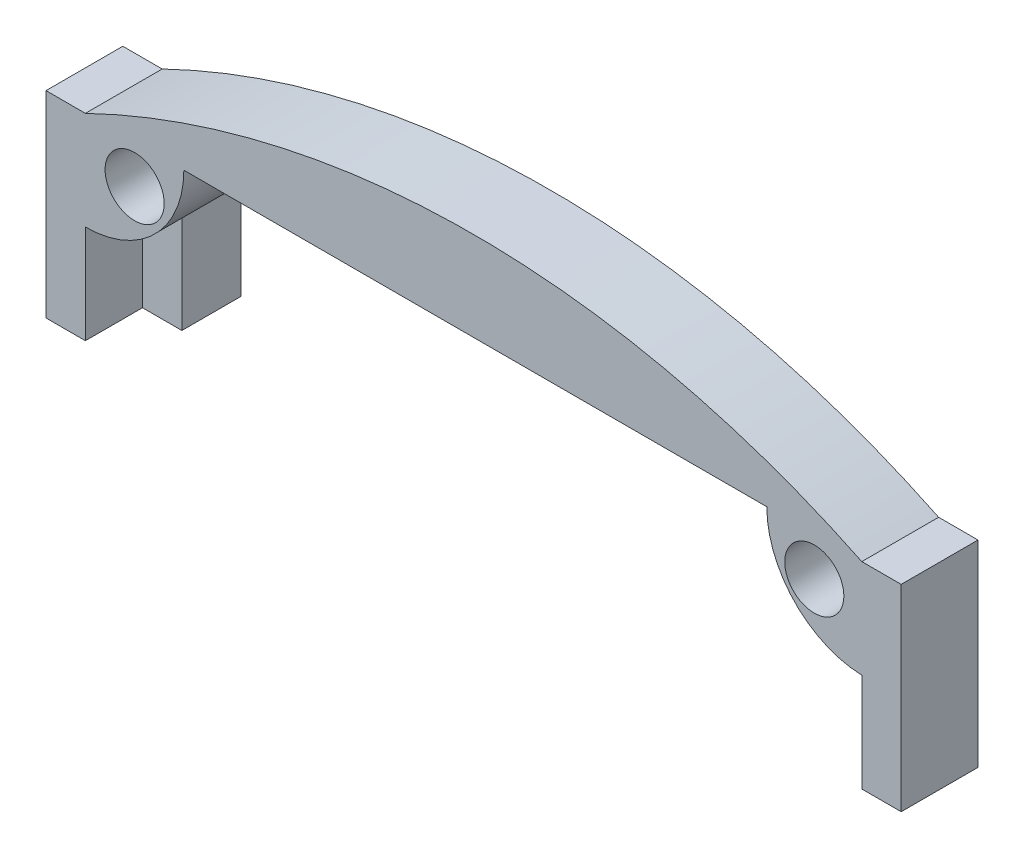
SolidWorks part; units mm, degrees
ref_plane "Alzado" through (0, 0, 0) normal (0, 0, 1) x (1, 0, 0)
ref_plane "Planta" through (0, 0, 0) normal (0, 1, 0) x (1, 0, 0)
ref_plane "Vista lateral" through (0, 0, 0) normal (1, 0, 0) x (0, 0, -1)
sketch "Croquis1" plane through (0, 0, 0) normal (0, 0, 1) x (1, 0, 0)
  line L0 (0, 0) -> (39.4233, 0)
  line L1 (0, 0) -> (0, -5)
  line L4 (39.4233, 0) -> (39.4233, -4.9969)
  line L5 (0, 0) -> (0, 2)
  line L7 (39.4233, 2) -> (39.4233, 0)
  line L8 (39.4233, 2) -> (39.4233, -4.9969) construction
  line L9 (34.6, -5) -> (34.6, 2) construction
  line L10 (34.6, 2) -> (39.4233, 2) construction
  line L11 (39.4233, 2) -> (37.0117, 2) construction
  line L12 (37.0117, 2) -> (37.0117, -1.972) construction
  line L13 (0, 2) -> (0, -5) construction
  line L14 (5, -5) -> (5, 2) construction
  line L15 (5, 2) -> (0, 2) construction
  line L16 (0, 2) -> (2.5, 2) construction
  line L17 (2.5, 2) -> (2.5, -1.972) construction
  arc A0 (0, -5) -> (5, 0) centre (0, 0) ccw
  arc A1 (39.4233, -4.9969) -> (34.6, 0) centre (39.6, 0) cw
  circle A2 centre (37.0117, -1.972) radius 1.5
  circle A3 centre (2.5, -1.972) radius 1.5
  arc A4 (0, 0) -> (39.4233, 0) centre (19.7117, -40.5877) cw
extrude "Saliente-Extruir1" add sketch "Croquis1" along normal blind 3.9
sketch3d "Croquis3D3"
  line L8 (39.4233, 0, 0) -> (41.4233, 0, 0)
  line L9 (41.4233, 0, 0) -> (41.4233, -10, 0)
  line L10 (41.4233, -10, 0) -> (39.4233, -10, 0)
  line L11 (39.4233, -10, 0) -> (39.4233, 0, 0)
  line L12 (0, 0, 0) -> (-2, 0, 0)
  line L13 (-2, 0, 0) -> (-2, -10, 0)
  line L14 (-2, -10, 0) -> (0, -10, 0)
  line L15 (0, -10, 0) -> (0, 0, 0)
extrude "Saliente-Extruir2" add sketch "Croquis3D3" along direction (0, 0, 1) on the side of the normal blind 3.9
sketch3d "Croquis3D4"
  line L0 (39.4233, -4.9969, 0) -> (37.6, -4.9969, 0)
  line L1 (37.6, -4.9969, 0) -> (37.6, -10, 0)
  line L2 (37.6, -10, 0) -> (39.4233, -10, 0)
  line L3 (39.4233, -10, 0) -> (39.4233, -4.9969, 0)
  line L4 (0, -10, 0) -> (0, -5, 0)
  line L5 (0, -5, 0) -> (2, -5, 0)
  line L6 (2, -5, 0) -> (2, -10, 0)
  line L7 (2, -10, 0) -> (0, -10, 0)
extrude "Saliente-Extruir4" add sketch "Croquis3D4" along direction (0, 0, 1) on the side of the normal blind 1 and the other way blind 2 separate body
